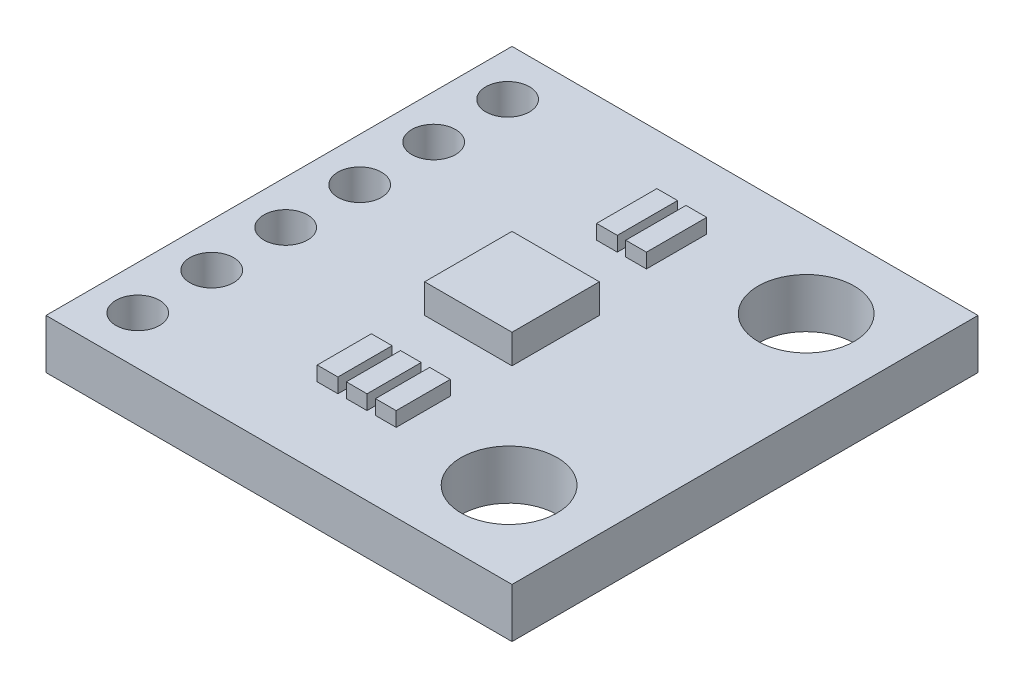
SolidWorks part; units mm, degrees
ref_plane "Front Plane" through (0, 0, 0) normal (0, 0, 1) x (1, 0, 0)
ref_plane "Top Plane" through (0, 0, 0) normal (0, 1, 0) x (1, 0, 0)
ref_plane "Right Plane" through (0, 0, 0) normal (1, 0, 0) x (0, 0, -1)
sketch "Sketch2" plane through (0, 0, 0) normal (0, 1, 0) x (1, 0, 0)
  line L1 (-8, -8) -> (8, -8)
  line L2 (-8, -8) -> (-8, 8)
  line L3 (-8, 8) -> (8, 8)
  line L4 (8, -8) -> (8, 8)
  line L5 (-8, -8) -> (8, 8) construction
  line L6 (-8, 8) -> (8, -8) construction
  point P0 (0, 0)
  dimension "D1" = 16
extrude "Boss-Extrude1" add sketch "Sketch2" along normal blind 1.7
sketch "Sketch3" plane through (0, 1.7, 0) normal (0, 1, 0) x (1, 0, 0)
  line L0 (-6.5, 6.35) -> (-6.5, -6.35) construction
  line L1 (-8, 8) -> (-8, -8) construction
  circle A0 centre (-6.5, 6.35) radius 0.75
  circle A1 centre (-6.5, 3.81) radius 0.75
  circle A2 centre (-6.5, 1.27) radius 0.75
  circle A3 centre (-6.5, -1.27) radius 0.75
  circle A4 centre (-6.5, -3.81) radius 0.75
  circle A5 centre (-6.5, -6.35) radius 0.75
  point P2 (-6.5, 0)
  dimension "D1" = 1.5
  dimension "D3" = 1.5
  dimension "D4" = 2.54
  dimension "D2" = 6
extrude "Cut-Extrude1" cut sketch "Sketch3" against normal blind 1.7 contours A0
sketch "Sketch4" plane through (0, 1.7, 0) normal (0, 1, 0) x (1, 0, 0)
  line L1 (-1.5, -1.5) -> (1.5, -1.5)
  line L2 (-1.5, -1.5) -> (-1.5, 1.5)
  line L3 (-1.5, 1.5) -> (1.5, 1.5)
  line L4 (1.5, -1.5) -> (1.5, 1.5)
  line L5 (-1.5, -1.5) -> (1.5, 1.5) construction
  line L6 (-1.5, 1.5) -> (1.5, -1.5) construction
  point P0 (0, 0)
  dimension "D1" = 3
extrude "Boss-Extrude2" add sketch "Sketch4" along normal blind 1
sketch "Sketch5" plane through (0, 1.7, 0) normal (0, 1, 0) x (1, 0, 0)
  line L0 (0.2163, 5.7579) -> (0.9269, 5.7579)
  line L1 (-0.7837, 5.7579) -> (-0.0731, 5.7579)
  line L2 (-0.7837, 5.7579) -> (-0.7837, 3.6888)
  line L3 (-0.7837, 3.6888) -> (-0.0731, 3.6888)
  line L4 (-0.0731, 5.7579) -> (-0.0731, 3.6888)
  line L5 (-1.3689, -3.4589) -> (-0.6583, -3.4589)
  line L6 (-1.3689, -3.4589) -> (-1.3689, -5.319)
  line L7 (-1.3689, -5.319) -> (-0.6583, -5.319)
  line L8 (-0.6583, -3.4589) -> (-0.6583, -5.319)
  line L9 (0.2163, 5.7579) -> (0.2163, 3.6888)
  line L10 (0.2163, 3.6888) -> (0.9269, 3.6888)
  line L11 (0.9269, 5.7579) -> (0.9269, 3.6888)
  line L12 (-0.3689, -3.4589) -> (0.3417, -3.4589)
  line L13 (-0.3689, -3.4589) -> (-0.3689, -5.319)
  line L14 (-0.3689, -5.319) -> (0.3417, -5.319)
  line L15 (0.3417, -3.4589) -> (0.3417, -5.319)
  line L16 (0.6311, -3.4589) -> (1.3417, -3.4589)
  line L17 (0.6311, -3.4589) -> (0.6311, -5.319)
  line L18 (0.6311, -5.319) -> (1.3417, -5.319)
  line L19 (1.3417, -3.4589) -> (1.3417, -5.319)
  dimension "D1" = 2
  dimension "D2" = 3
extrude "Boss-Extrude3" add sketch "Sketch5" along normal blind 0.5
sketch "Sketch6" plane through (0, 1.7, 0) normal (0, 1, 0) x (1, 0, 0)
  line L0 (0, 0) -> (9.3945, 0) construction
  circle A0 centre (5, 5.1) radius 1.65
  circle A1 centre (5, -5.1) radius 1.65
  circle A2 centre (-6.5, 6.35) radius 0.75 construction
  dimension "D1" = 3.3
  dimension "D2" = 5.1
  dimension "D3" = 11.5
extrude "Cut-Extrude2" cut sketch "Sketch6" against normal through all
